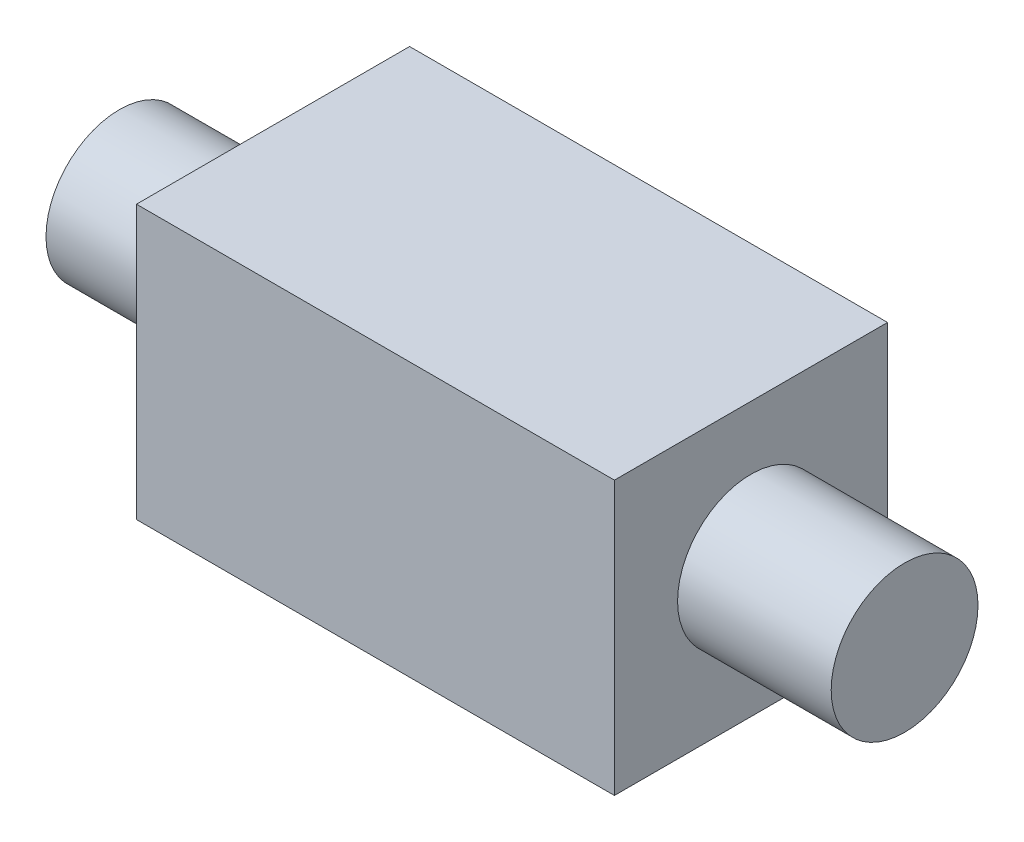
SolidWorks part; units mm, degrees
ref_plane "Front Plane" through (0, 0, 0) normal (0, 0, 1) x (1, 0, 0)
ref_plane "Top Plane" through (0, 0, 0) normal (0, 1, 0) x (1, 0, 0)
ref_plane "Right Plane" through (0, 0, 0) normal (1, 0, 0) x (0, 0, -1)
sketch "Sketch1" plane through (0, 0, 0) normal (0, 1, 0) x (1, 0, 0)
  line L1 (10.8052, 9.6753) -> (24.8052, 9.6753)
  line L2 (10.8052, 9.6753) -> (10.8052, 1.6753)
  line L3 (10.8052, 1.6753) -> (24.8052, 1.6753)
  line L4 (24.8052, 9.6753) -> (24.8052, 1.6753)
  dimension "D1" = 14
  dimension "D2" = 8
extrude "Boss-Extrude1" add sketch "Sketch1" along normal blind 8
ref_plane "Plane1" through (24.8052, 0, 0) normal (1, 0, 0) x (0, 0, -1)
sketch "Sketch3" plane through (24.8052, 0, 0) normal (1, 0, 0) x (0, 0, -1)
  line L0 (1.6753, 0) -> (9.6753, 0) construction
  line L1 (1.6753, 8) -> (1.6753, 0) construction
  circle A0 centre (5.6753, 4) radius 2.15
  dimension "D1" = 4.3
  dimension "D2" = 4
  dimension "D3" = 4
extrude "Boss-Extrude3" add sketch "Sketch3" along normal blind 4.5
ref_plane "Plane2" through (10.8052, 0, 0) normal (-1, 0, 0) x (0, 0, 1)
sketch "Sketch4" plane through (10.8052, 0, 0) normal (-1, 0, 0) x (0, 0, 1)
  line L0 (-1.6753, 8) -> (-1.6753, 0) construction
  line L1 (-9.6753, 0) -> (-1.6753, 0) construction
  circle A0 centre (-5.6753, 4) radius 2.15
  dimension "D1" = 4.3
  dimension "D2" = 4
  dimension "D3" = 4
extrude "Boss-Extrude4" add sketch "Sketch4" along normal blind 4.5
